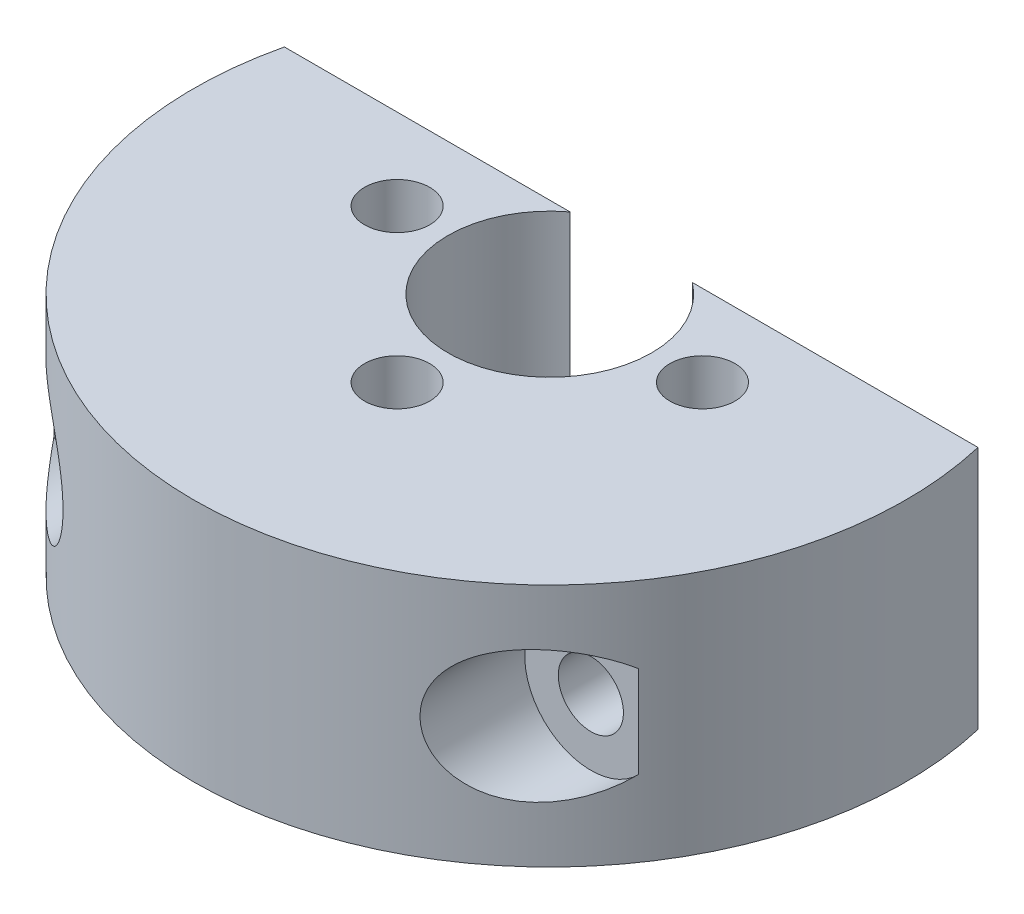
SolidWorks part; units mm, degrees
ref_plane "Front Plane" through (0, 0, 0) normal (0, 0, 1) x (1, 0, 0)
ref_plane "Top Plane" through (0, 0, 0) normal (0, 1, 0) x (1, 0, 0)
ref_plane "Right Plane" through (0, 0, 0) normal (1, 0, 0) x (0, 0, -1)
sketch "Sketch1" plane through (0, 0, 0) normal (0, 1, 0) x (1, 0, 0)
  circle A0 centre (0, 0) radius 17.5
  circle A1 centre (0, 0) radius 5
  dimension "D1" = 35
  dimension "D2" = 10
extrude "Boss-Extrude1" add sketch "Sketch1" along normal blind 12
ref_plane "Plane1" through (0, 0, -4) normal (0, 0, 1) x (1, 0, 0)
sketch "Sketch2" plane through (0, 0, -4) normal (0, 0, 1) x (1, 0, 0)
  line L1 (-20.0274, 15) -> (19.9726, 15)
  line L2 (-20.0274, 15) -> (-20.0274, 0)
  line L3 (-20.0274, 0) -> (19.9726, 0)
  line L4 (19.9726, 15) -> (19.9726, 0)
  dimension "D1" = 40
  dimension "D2" = 15
extrude "Cut-Extrude1" cut sketch "Sketch2" against normal up to next
sketch "Sketch3" plane through (0, 0, -4) normal (0, 0, -1) x (-1, 0, 0)
  line L4 (-17.0367, 12) -> (-7, 12) construction
  line L5 (-17.0367, 12) -> (-17.0367, 0) construction
  line L6 (-17.0367, 0) -> (-7, 0) construction
  line L7 (-7, 12) -> (-7, 0) construction
  line L8 (-17.0367, 0) -> (-3, 0) construction
  line L10 (-3, 12) -> (-3, 0) construction
  line L11 (-17.0367, 12) -> (-7, 0) construction
  line L14 (17.0367, 12) -> (7, 12) construction
  line L15 (17.0367, 12) -> (17.0367, 0) construction
  line L16 (17.0367, 0) -> (7, 0) construction
  line L17 (7, 12) -> (7, 0) construction
  line L18 (3, 0) -> (17.0367, 0) construction
  line L19 (3, 0) -> (3, 12) construction
  line L20 (7, 12) -> (17.0367, 0) construction
  circle A0 centre (-12.0184, 6) radius 1.6
  circle A1 centre (12.0184, 6) radius 1.6
  point P1237 (-12.0184, 6)
  point P1472 (0, 0)
  point P1473 (12.0184, 6)
  dimension "D1" = 3.2
  dimension "D2" = 4
  dimension "D3" = 4
extrude "Cut-Extrude2" cut sketch "Sketch3" against normal up to next
ref_plane "Plane2" through (0, 0, 17.5) normal (0, 0, 1) x (1, 0, 0)
sketch "Sketch5" plane through (0, 0, 17.5) normal (0, 0, 1) x (1, 0, 0)
  circle A0 centre (-12.0184, 6) radius 3.25
  circle A1 centre (12.0184, 6) radius 3.25
  dimension "D1" = 6.5
ref_plane "Plane3" through (0, 0, 10) normal (0, 0, 1) x (1, 0, 0)
extrude "Cut-Extrude3" cut sketch "Sketch5" along direction (0, 0, 1) on the side against the normal up to surface (7.5 mm away) up to plane "Plane3"
sketch "Sketch7" plane through (0, 12, 0) normal (0, 1, 0) x (1, 0, 0)
  circle A0 centre (0, 0) radius 12 construction
  dimension "D1" = 24
sketch "Sketch8" plane through (0, 12, 0) normal (0, 1, 0) x (1, 0, 0)
  circle A0 centre (-7.5, 0) radius 1.6
  circle A1 centre (7.5, 0) radius 1.6
  circle A2 centre (0, 0) radius 7.5 construction
  circle A8 centre (0, -7.5) radius 1.6
  dimension "D1" = 3.2
  dimension "D2" = 15
extrude "Cut-Extrude4" cut sketch "Sketch8" against normal through all
